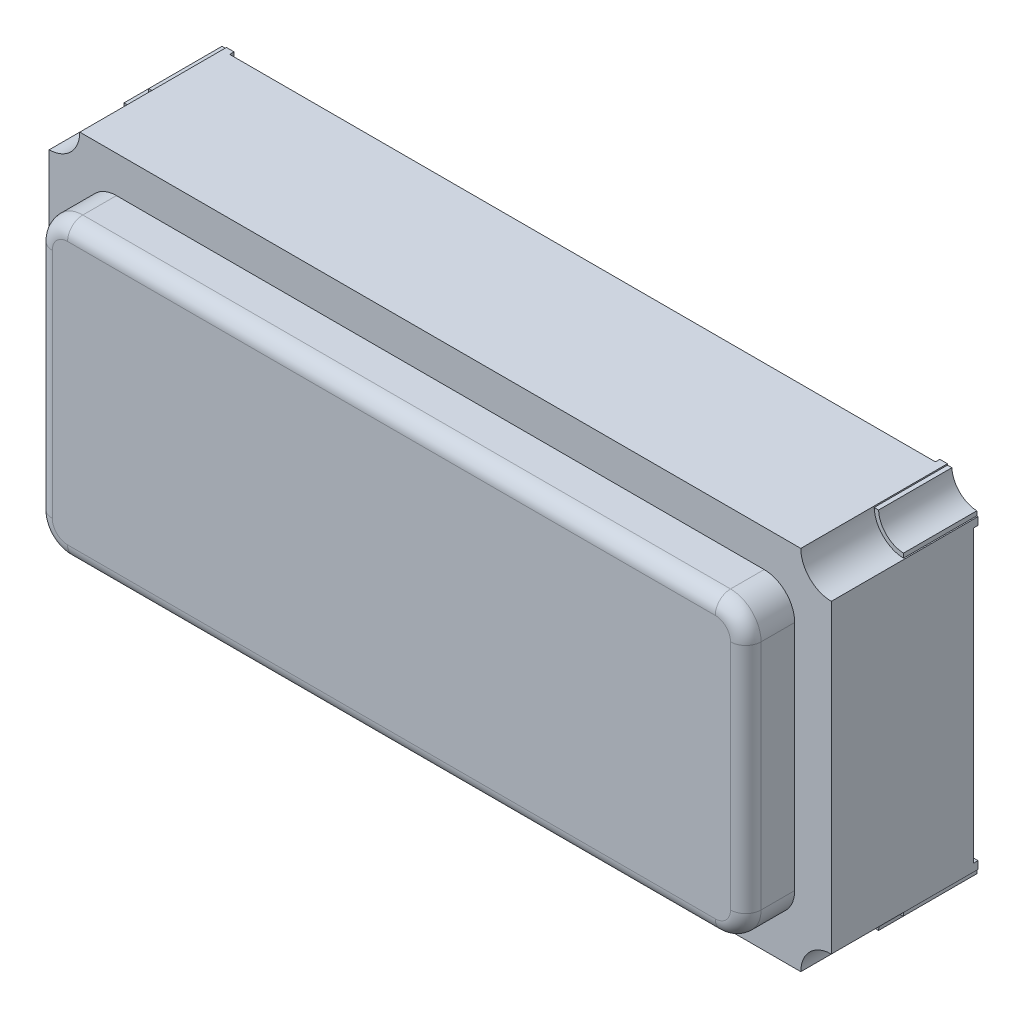
SolidWorks part; units mm, degrees
ref_plane "Front Plane" through (0, 0, 0) normal (0, 0, 1) x (1, 0, 0)
ref_plane "Top Plane" through (0, 0, 0) normal (0, 1, 0) x (1, 0, 0)
ref_plane "Right Plane" through (0, 0, 0) normal (1, 0, 0) x (0, 0, -1)
sketch "Sketch1" plane through (0, 0, 0) normal (0, 0, 1) x (1, 0, 0)
  line L1 (-1.6, 0.75) -> (1.6, 0.75)
  line L2 (-1.6, 0.75) -> (-1.6, -0.75)
  line L3 (-1.6, -0.75) -> (1.6, -0.75)
  line L4 (1.6, 0.75) -> (1.6, -0.75)
  line L5 (-1.6, 0.75) -> (1.6, -0.75) construction
  line L6 (-1.6, -0.75) -> (1.6, 0.75) construction
  point P0 (0, 0)
  dimension "D1" = 3.2
  dimension "D2" = 1.5
extrude "Boss-Extrude1" add sketch "Sketch1" along normal blind 0.564 contours L1 L4 L3 L2
sketch "Sketch2" plane through (0, 0, 0) normal (0, 0, -1) x (-1, 0, 0)
  line L18 (1.4438, -0.7) -> (0.8, -0.7)
  line L19 (1.55, -0.5938) -> (1.55, 0)
  line L20 (1.55, 0) -> (0.8, 0)
  line L21 (0.8, -0.7) -> (0.8, 0)
  line L35 (1.6, -0.75) -> (-1.6, -0.75) construction
  line L37 (1.4438, -0.7) -> (1.4438, -0.75)
  line L38 (1.55, -0.5938) -> (1.6, -0.5938)
  line L39 (1.6, 0.75) -> (1.6, -0.75) construction
  line L40 (1.6, -0.5938) -> (1.6, -0.75)
  line L41 (1.6, -0.75) -> (1.4438, -0.75)
  point P1 (0, 0)
  point P5 (1.6, 0)
  point P6 (1.5026, -0.4996)
  point P7 (0, 0)
  point P8 (1.55, 0)
  dimension "D2" = 0.7
  dimension "D7" = 0.1562
  dimension "D1" = 0.75
extrude "Boss-Extrude2" add sketch "Sketch2" along normal blind 0.018
mirror "Mirror4" about plane through (0, 0, 0) normal (0, 1, 0) of "Boss-Extrude2"
mirror "Mirror5" about plane through (0, 0, 0) normal (1, 0, 0) of "Mirror4", "Boss-Extrude2"
sketch "Sketch3" plane through (0, 0, 0) normal (0, 0, -1) x (-1, 0, 0)
  line L0 (1.475, -0.75) -> (-1.475, -0.75) construction
  line L1 (1.4438, -0.75) -> (-1.4438, -0.75) construction
  line L2 (1.6, -0.625) -> (1.6, 0.625) construction
  line L3 (1.6, 0.5938) -> (1.6, -0.5937) construction
  line L4 (1.475, 0.75) -> (-1.475, 0.75) construction
  line L5 (1.4438, 0.75) -> (-1.4437, 0.75) construction
  line L6 (-1.6, -0.625) -> (-1.6, 0.625) construction
  line L7 (-1.6, 0.5938) -> (-1.6, -0.5938) construction
  line L8 (1.6, 0.625) -> (1.6, 0.75)
  line L9 (1.6, 0.75) -> (1.475, 0.75)
  line L10 (-1.475, 0.75) -> (-1.6, 0.75)
  line L11 (-1.6, 0.75) -> (-1.6, 0.625)
  line L12 (-1.6, -0.625) -> (-1.6, -0.75)
  line L13 (-1.6, -0.75) -> (-1.475, -0.75)
  line L14 (1.6, -0.625) -> (1.6, -0.75)
  line L15 (1.6, -0.75) -> (1.475, -0.75)
  arc A0 (1.6, -0.625) -> (1.475, -0.75) centre (1.6, -0.75) ccw
  arc A1 (-1.475, -0.75) -> (-1.6, -0.625) centre (-1.6, -0.75) ccw
  arc A2 (-1.475, 0.75) -> (-1.6, 0.625) centre (-1.6, 0.75) cw
  arc A3 (1.6, 0.625) -> (1.475, 0.75) centre (1.6, 0.75) cw
  point P16 (0, -0.75)
  point P17 (0, 0.75)
  point P19 (-1.6, 0)
  point P20 (1.6, 0)
  dimension "D1" = 0.125
extrude "Cut-Extrude1" cut sketch "Sketch3" against normal through all both and the other way through all
sketch "Sketch5" plane through (0, 0, 0) normal (0, 0, -1) x (-1, 0, 0)
  line L0 (1.4751, -0.745) -> (1.4931, -0.745)
  line L1 (1.595, -0.6251) -> (1.595, -0.6431)
  line L2 (1.4438, -0.75) -> (-1.4438, -0.75) construction
  arc A0 (1.595, -0.6251) -> (1.4751, -0.745) centre (1.6, -0.75) ccw
  arc A1 (1.6, -0.625) -> (1.475, -0.75) centre (1.6, -0.75) ccw construction
  arc A2 (1.595, -0.6431) -> (1.4931, -0.745) centre (1.6, -0.75) ccw
  arc A3 (1.6, -0.625) -> (1.475, -0.75) centre (1.6, -0.75) ccw construction
  point P15 (1.5116, -0.6616)
  point P19 (1.5116, -0.6616)
  dimension "D2" = 0.005
extrude "Boss-Extrude3" add sketch "Sketch5" against normal blind 0.282 and the other way through all
mirror "Mirror1" about plane through (0, 0, 0) normal (1, 0, 0) of "Boss-Extrude3"
mirror "Mirror2" about plane through (0, 0, 0) normal (0, 1, 0) of "Mirror1", "Boss-Extrude3"
sketch "Sketch7" plane through (0, 0, 0.564) normal (0, 0, 1) x (1, 0, 0)
  line L0 (-1.6, 0.625) -> (-1.6, -0.625) construction
  line L1 (-1.475, 0.75) -> (1.475, 0.75)
  line L2 (1.6, 0.625) -> (1.6, -0.625)
  line L3 (1.475, -0.75) -> (-1.475, -0.75)
  line L4 (-1.6, -0.625) -> (-1.6, 0.625)
  arc A0 (-1.6, -0.625) -> (-1.475, -0.75) centre (-1.6, -0.75) cw
  arc A1 (-1.475, -0.75) -> (-1.6, -0.625) centre (-1.6, -0.75) ccw construction
  arc A2 (1.475, -0.75) -> (1.6, -0.625) centre (1.6, -0.75) cw
  arc A3 (1.6, -0.625) -> (1.475, -0.75) centre (1.6, -0.75) ccw construction
  arc A4 (1.475, 0.75) -> (1.6, 0.625) centre (1.6, 0.75) ccw
  arc A5 (1.475, 0.75) -> (1.6, 0.625) centre (1.6, 0.75) ccw construction
  arc A6 (-1.475, 0.75) -> (-1.6, 0.625) centre (-1.6, 0.75) cw
  arc A7 (-1.6, 0.625) -> (-1.475, 0.75) centre (-1.6, 0.75) ccw construction
extrude "Boss-Extrude4" add sketch "Sketch7" along normal blind 0.018
sketch "Sketch8" plane through (0, 0, 0.582) normal (0, 0, 1) x (1, 0, 0)
  line L0 (-1.6, 0.625) -> (-1.6, -0.625) construction
  line L1 (-1.45, 0.6) -> (1.45, 0.6)
  line L2 (-1.45, 0.6) -> (-1.45, -0.6)
  line L3 (-1.45, -0.6) -> (1.45, -0.6)
  line L4 (1.45, 0.6) -> (1.45, -0.6)
  line L5 (-1.45, 0.6) -> (1.45, -0.6) construction
  line L6 (-1.45, -0.6) -> (1.45, 0.6) construction
  line L7 (1.475, 0.75) -> (-1.475, 0.75) construction
  point P0 (0, 0)
  dimension "D1" = 0.15
  dimension "D2" = 0.15
extrude "Boss-Extrude5" add sketch "Sketch8" along normal blind 0.2
fillet "Fillet1" radius 0.125 4 edges at (-1.45, 0.6, 0.682) (1.45, 0.6, 0.682) (1.45, -0.6, 0.682) (-1.45, -0.6, 0.682)
fillet "Fillet2" radius 0.0625 8 edges at (1.4134, 0.5634, 0.782) (1.45, 0, 0.782) (1.4134, -0.5634, 0.782) (0, -0.6, 0.782) (-1.4134, -0.5634, 0.782) (-1.45, 0, 0.782) (-1.4134, 0.5634, 0.782) (0, 0.6, 0.782)
chamfer "Chamfer1" distance 0.25 angle 45 1 edges at (-0.8, -0.7, -0.009)
equation "\"W\"= 3.2"
equation "\"L\"= 1.5"
equation "\"D1@Sketch1\"=\"W\""
equation "\"D2@Sketch1\"=\"L\""
equation "\"H\"= 0.8"
equation "\"D1@Boss-Extrude1\"=\"H_base\""
equation "\"H_shield\"= 0.2"
equation "\"H_contact\"= 0.018"
equation "\"H_base\"= \"H\" - \"H_shield\" - 2 * \"H_contact\""
equation "\"X_contact_spacing\"= 1.2"
equation "\"Y_contact_spacing\"= 0.9"
equation "\"W_contact\"= 0.75"
equation "\"L_contact\"= 0.7"
equation "\"D2@Sketch2\"=\"L_contact\""
equation "\"D1@Boss-Extrude2\"=\"H_contact\""
equation "\"Chamfer_contact\"= 0.25"
equation "\"R\" = 0.125"
equation "\"D7@Sketch2\"=\"R\"*1.25"
equation "\"D1@Sketch5\"=\"H_contact\""
equation "\"D1@Boss-Extrude3\"=\"H_base\"/2"
equation "\"D1@Sketch3\"=\"R\""
equation "\"D1@Boss-Extrude4\"=\"H_contact\""
equation "\"D2@Sketch8\"=\"D1@Sketch8\""
equation "\"D1@Boss-Extrude5\"=\"H_shield\""
equation "\"D1@Fillet1\"=\"R\""
equation "\"D1@Fillet2\"=\"R\"/2"
equation "\"D1@Sketch2\"=\"W_contact\""
